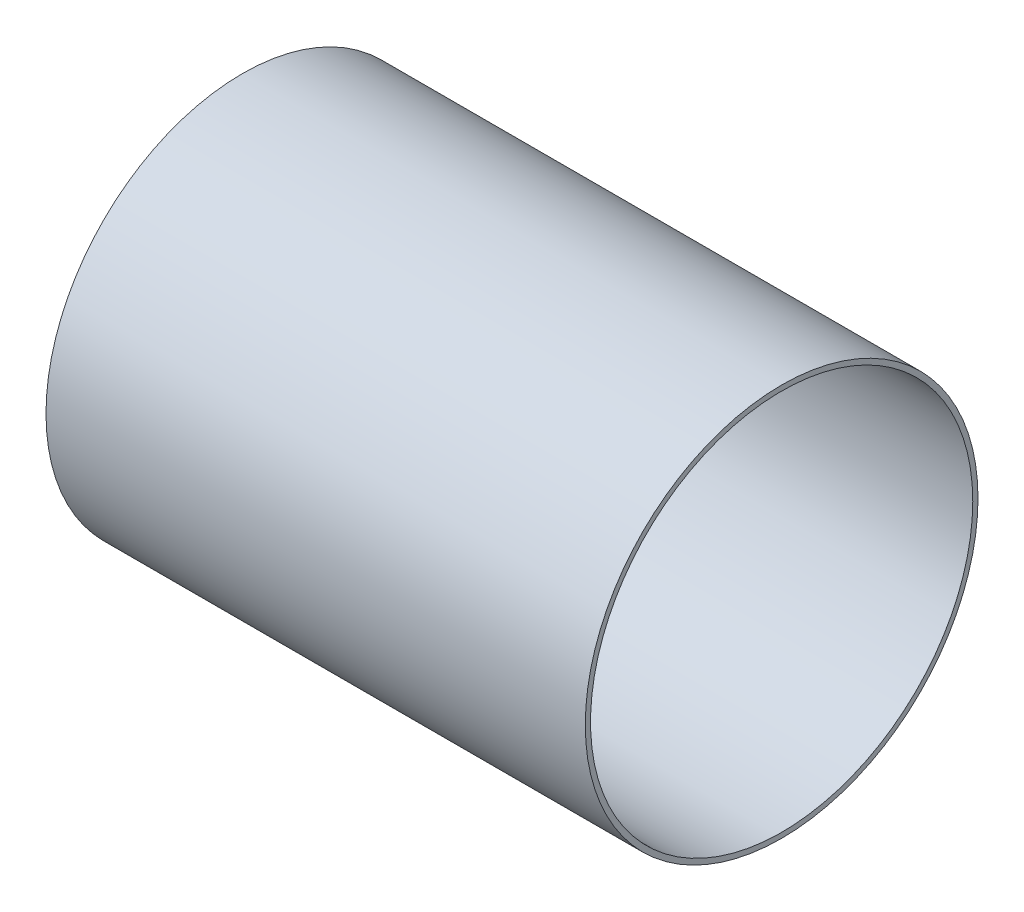
SolidWorks part; units mm, degrees
material "PA12CF"
ref_plane "Płaszczyzna przednia" through (0, 0, 0) normal (0, 0, 1) x (1, 0, 0)
ref_plane "Płaszczyzna górna" through (0, 0, 0) normal (0, 1, 0) x (1, 0, 0)
ref_plane "Płaszczyzna prawa" through (0, 0, 0) normal (1, 0, 0) x (0, 0, -1)
sketch "Sketch1" plane through (0, 0, 0) normal (1, 0, 0) x (0, 0, -1)
  circle A0 centre (0, 0) radius 75
  circle A1 centre (0, 0) radius 73
  dimension "D1" = 150
  dimension "D2" = 2
extrude "Boss-Extrude1" add sketch "Sketch1" along normal blind 206
